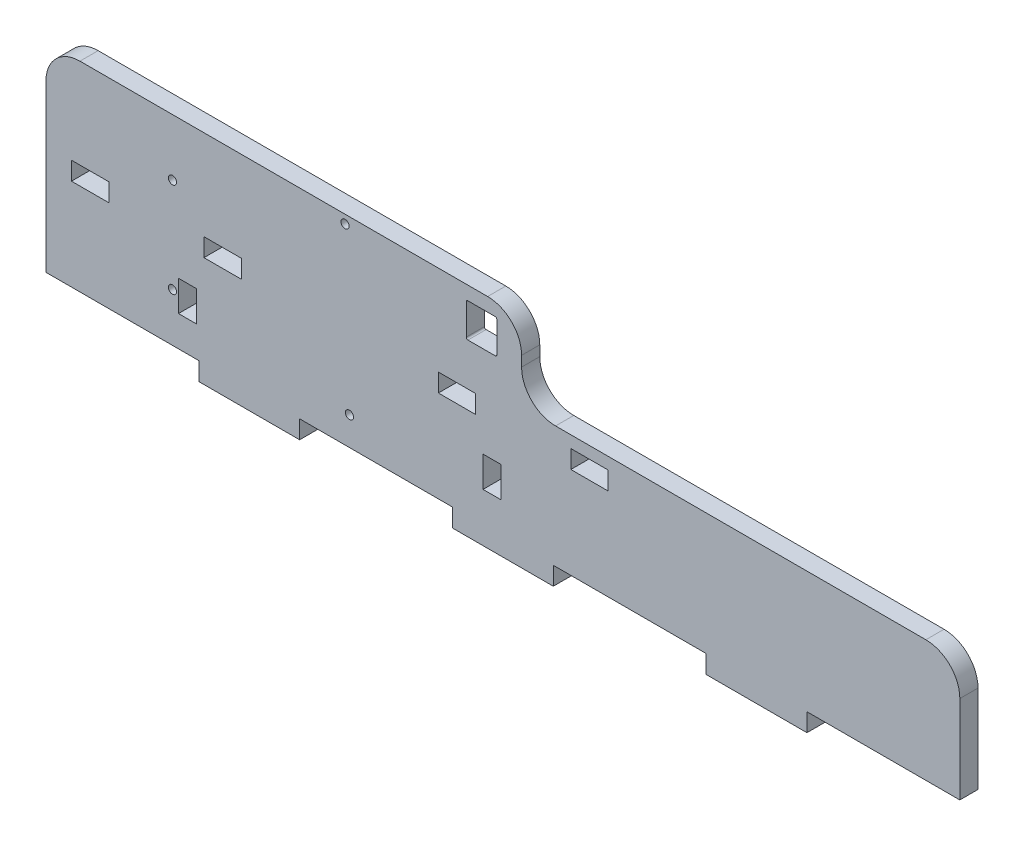
SolidWorks part; units mm, degrees
ref_plane "Front Plane" through (0, 0, 0) normal (0, 0, 1) x (1, 0, 0)
ref_plane "Top Plane" through (0, 0, 0) normal (0, 1, 0) x (1, 0, 0)
ref_plane "Right Plane" through (0, 0, 0) normal (1, 0, 0) x (0, 0, -1)
sketch "Model" plane through (0, 0, 0) normal (0, 0, 1) x (1, 0, 0)
  line L0 (269, 5) -> (0, 5) construction
  line L1 (0, 0) -> (45.001, 0)
  line L2 (0, 0) -> (0, 48.85)
  line L3 (150, 35.85) -> (259, 35.85)
  line L4 (269, 0) -> (269, 25.85)
  line L5 (134.5, 5) -> (134.5, -32.0534) construction
  line L6 (37.23, 42.15) -> (37.23, -13.65) construction
  line L7 (10, 58.85) -> (130, 58.85)
  line L8 (140, 45.85) -> (140, 48.85)
  line L9 (149.333, 0) -> (194.333, 0)
  line L10 (194.333, 0) -> (194.333, -5.35)
  line L11 (119.667, 0) -> (119.667, -5.35)
  line L12 (119.667, -5.35) -> (149.333, -5.35)
  line L13 (149.333, 0) -> (149.333, -5.35)
  line L14 (194.333, -5.35) -> (223.999, -5.35)
  line L15 (223.999, 0) -> (223.999, -5.35)
  line L16 (223.999, 0) -> (269, 0)
  line L17 (45.001, 0) -> (45.001, -5.35)
  line L18 (45.001, -5.35) -> (74.667, -5.35)
  line L19 (74.667, 0) -> (74.667, -5.35)
  line L20 (74.667, 0) -> (119.667, 0)
  line L21 (7.5, 32.35) -> (18.5, 32.35)
  line L22 (7.5, 32.35) -> (7.5, 27)
  line L23 (7.5, 27) -> (18.5, 27)
  line L24 (18.5, 32.35) -> (18.5, 27)
  line L25 (46.5, 32.35) -> (57.5, 32.35)
  line L26 (46.5, 32.35) -> (46.5, 27)
  line L27 (46.5, 27) -> (57.5, 27)
  line L28 (57.5, 32.35) -> (57.5, 27)
  line L29 (115.5, 32.35) -> (126.5, 32.35)
  line L30 (115.5, 32.35) -> (115.5, 27)
  line L31 (115.5, 27) -> (126.5, 27)
  line L32 (126.5, 32.35) -> (126.5, 27)
  line L33 (154.5, 32.35) -> (165.5, 32.35)
  line L34 (154.5, 32.35) -> (154.5, 27)
  line L35 (154.5, 27) -> (165.5, 27)
  line L36 (165.5, 32.35) -> (165.5, 27)
  line L37 (39, 18) -> (44.35, 18)
  line L38 (39, 18) -> (39, 9)
  line L39 (39, 9) -> (44.35, 9)
  line L40 (44.35, 18) -> (44.35, 9)
  line L41 (128.65, 18) -> (134, 18)
  line L42 (128.65, 18) -> (128.65, 9)
  line L43 (128.65, 9) -> (134, 9)
  line L44 (134, 18) -> (134, 9)
  line L46 (124.21, 54.85) -> (132.21, 54.85)
  line L47 (123.71, 54.35) -> (123.71, 45.35)
  line L48 (124.21, 44.85) -> (132.21, 44.85)
  line L49 (132.71, 54.35) -> (132.71, 45.35)
  arc A0 (10, 58.85) -> (0, 48.85) centre (10, 48.85) ccw
  arc A1 (140, 48.85) -> (130, 58.85) centre (130, 48.85) ccw
  arc A2 (140, 45.85) -> (150, 35.85) centre (150, 45.85) ccw
  arc A3 (269, 25.85) -> (259, 35.85) centre (259, 25.85) ccw
  circle A4 centre (37.23, 42.15) radius 1.2
  circle A5 centre (88.03, 56.35) radius 1.2
  circle A6 centre (89.33, 8.35) radius 1.2
  circle A7 centre (37.23, 14.25) radius 1.2
  arc A8 (124.21, 54.85) -> (123.71, 54.35) centre (124.21, 54.35) ccw
  arc A9 (123.71, 45.35) -> (124.21, 44.85) centre (124.21, 45.35) ccw
  arc A10 (132.21, 44.85) -> (132.71, 45.35) centre (132.21, 45.35) ccw
  arc A11 (132.71, 54.35) -> (132.21, 54.85) centre (132.21, 54.35) ccw
  point P23 (134.5, -5.35)
  point P33 (59.834, -5.35)
  dimension "D5" = 10
  dimension "D56" = 2.4
  dimension "D72" = 1
  dimension "D9" = 23
  dimension "D14" = 129
  dimension "D16" = 29.666
  dimension "D17" = 5.35
  dimension "D22" = 45
  dimension "D23" = 45
  dimension "D24" = 10
  dimension "D10" = 269
  dimension "D6" = 58.85
  dimension "D26" = 5.35
  dimension "D27" = 11
  dimension "D29" = 26.5
  dimension "D31" = 7.5
  dimension "D34" = 28
  dimension "D35" = 28
  dimension "D37" = 58
  dimension "D40" = 5.35
  dimension "D43" = 9
  dimension "D46" = 9
  dimension "D48" = 39
  dimension "D51" = 84.3
  dimension "D58" = 37.23
  dimension "D60" = 16.7
  dimension "D63" = 2.5
  dimension "D65" = 50.8
  dimension "D67" = 48
  dimension "D69" = 52.1
  dimension "D73" = 9
  dimension "D74" = 10
  dimension "D76" = 4
  dimension "D78" = 7.29
  dimension "D80" = 14.25
  dimension "D19" = 2
  dimension "D20" = 2
extrude "Boss-Extrude1" add sketch "Model" along normal blind 5.35
equation "\"mdfthick\"=5.35"
equation "\"D17@Model\"=\"mdfthick\""
equation "\"D26@Model\"=\"mdfthick\""
equation "\"D40@Model\"=\"mdfthick\""
equation "\"D1@Boss-Extrude1\"=\"mdfthick\""
